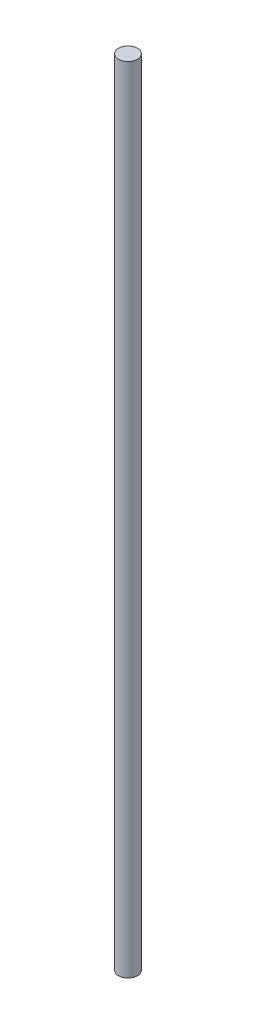
SolidWorks part; units mm, degrees
ref_plane "Front Plane" through (0, 0, 0) normal (0, 0, 1) x (1, 0, 0)
ref_plane "Top Plane" through (0, 0, 0) normal (0, 1, 0) x (1, 0, 0)
ref_plane "Right Plane" through (0, 0, 0) normal (1, 0, 0) x (0, 0, -1)
sketch "Sketch2" plane through (0, 0, 0) normal (0, 1, 0) x (1, 0, 0)
  circle A0 centre (0, 0) radius 3
  dimension "D1" = 6
extrude "Boss-Extrude1" add sketch "Sketch2" along normal blind 250
